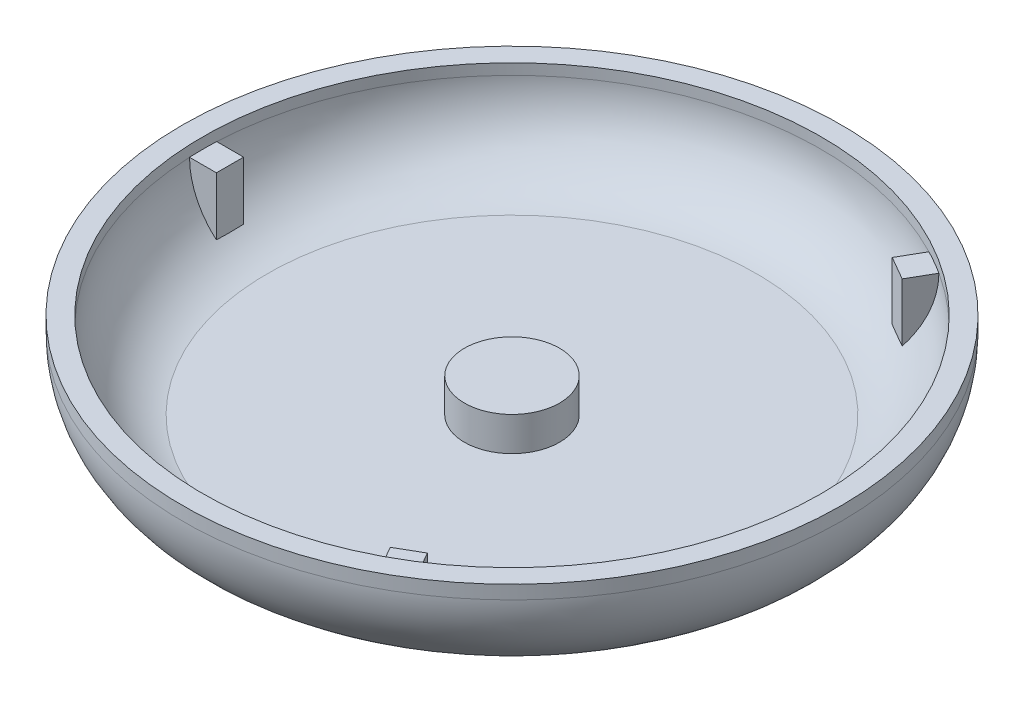
SolidWorks part; units mm, degrees
ref_plane "Front Plane" through (0, 0, 0) normal (0, 0, 1) x (1, 0, 0)
ref_plane "Top Plane" through (0, 0, 0) normal (0, 1, 0) x (1, 0, 0)
ref_plane "Right Plane" through (0, 0, 0) normal (1, 0, 0) x (0, 0, -1)
ref_plane "Plane1" through (0, 0, 0) normal (0, 1, 0) x (1, 0, 0)
sketch "Sketch2" plane through (0, 0, 0) normal (0, 1, 0) x (1, 0, 0)
  line L1 (0, 22.75) -> (0, -22.75) construction
  line L3 (22.75, 0) -> (-22.75, 0) construction
  circle A0 centre (0, 0) radius 22.75
  circle A3 centre (0, 0) radius 24.25
  dimension "D1" = 45.5
  dimension "D2" = 1.5
ref_plane "Plane2" through (0, 0, 0) normal (0, 0, 1) x (1, 0, 0)
sketch "Sketch3" plane through (0, 0, 0) normal (0, 0, 1) x (1, 0, 0)
  line L0 (-24.25, 0) -> (-24.25, -1)
  line L2 (0, -13.1985) -> (0, 4.5374) construction
  line L3 (-22.75, -0.8) -> (-22.75, 0) construction
  line L4 (0, -3.85) -> (-12.5, -3.85) construction
  line L5 (-22.75, 0) -> (-24.25, 0)
  line L6 (-22.75, 0) -> (-19.25, 0) construction
  line L8 (0, 0) -> (0, -3.85) construction
  line L9 (-12.5, -3.85) -> (-12.5, 0) construction
  line L10 (-22.75, 0) -> (-22.75, -0.8) construction
  line L11 (-22.75, 0) -> (-22.75, -0.8)
  line L12 (-3.5, -3.85) -> (0, -3.85)
  line L13 (-3.5, -3.85) -> (-3.5, -6.35)
  line L14 (0, -7.85) -> (-18, -7.85)
  line L15 (0, -3.85) -> (0, -7.85)
  line L18 (-19.25, -0.8) -> (-19.25, -5.8) construction
  line L19 (-22.75, -0.8) -> (-19.25, -0.8) construction
  line L20 (0, -5.85) -> (0, -6.35) construction
  line L21 (-3.5, -6.35) -> (-18, -6.35)
  arc A0 (-18, -6.35) -> (-22.75, -0.8) centre (-17.1326, -0.8) cw
  arc A1 (-24.25, -1) -> (-18, -7.85) centre (-17.3712, -1) ccw
  dimension "D2" = 1.5
  dimension "D7" = 1
  dimension "D3" = 0.8
  dimension "D5" = 3.85
  dimension "D6" = 18
  dimension "D8" = 12.5
  dimension "D11" = 2.5
  dimension "D12" = 3.5
  dimension "D15" = 5
  dimension "D17" = 18
ref_plane "Plane3" through (0, -7.85, 0) normal (0, 1, 0) x (1, 0, 0)
ref_plane "Plane4" through (0, -0.8, 0) normal (0, 1, 0) x (1, 0, 0)
sketch "Sketch4" plane through (0, -0.8, 0) normal (0, 1, 0) x (1, 0, 0)
  line L0 (-22.75, 0) -> (-20.75, 0) construction
  line L1 (-22.75, 1) -> (-20.75, 1)
  line L2 (-22.75, 1) -> (-22.75, -1)
  line L3 (-22.75, -1) -> (-20.75, -1)
  line L4 (-20.75, 1) -> (-20.75, -1)
  dimension "D1" = 2
  dimension "D2" = 2
sketch "Sketch7" plane through (0, 0, 0) normal (0, 1, 0) x (1, 0, 0)
  circle A0 centre (0, 0) radius 22.75
  circle A1 centre (0, 0) radius 22.75 construction
revolve "Revolve1" add sketch "Sketch3" angle 360 about L2
extrude "Boss-Extrude2" add sketch "Sketch4" against normal up to surface contours L3 L4 L1 L2 up to face at (22.75, -0.8, 0)
pattern_circular "CirPattern2" count 3 every 120 about axis through (0, 0, 0) along (0, 1, 0) of "Boss-Extrude2"
